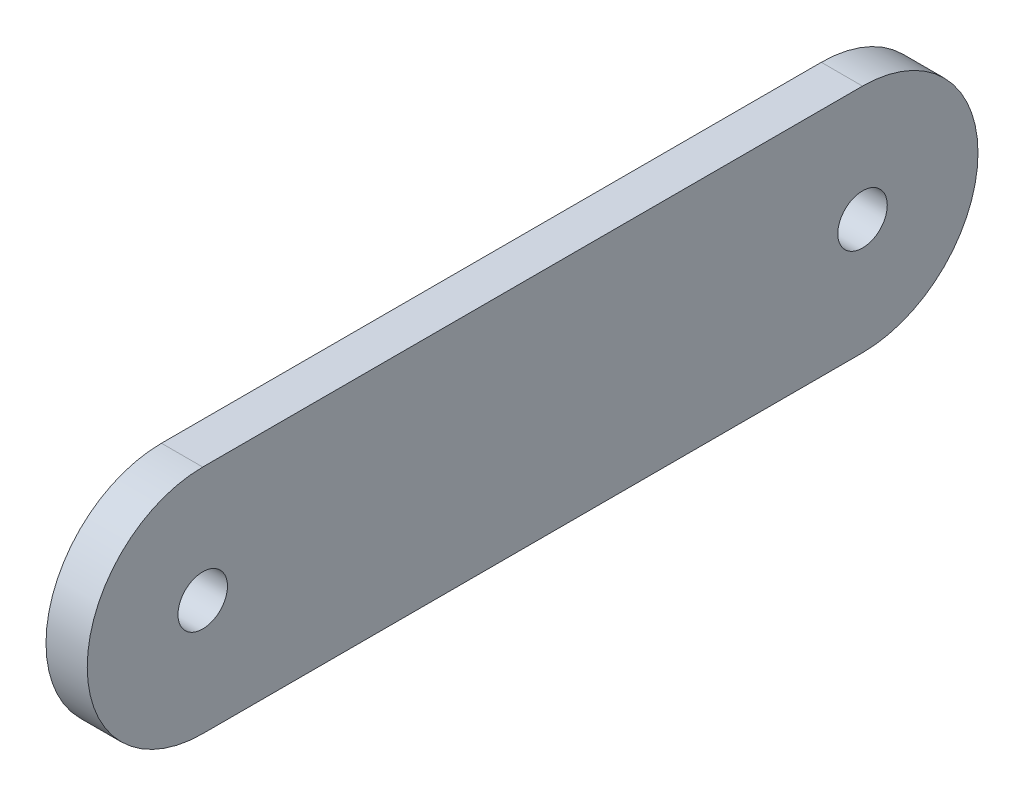
SolidWorks part; units mm, degrees
ref_plane "Ground" through (0, 0, 0) normal (0, 0, 1) x (1, 0, 0)
ref_plane "Right" through (0, 0, 0) normal (0, 1, 0) x (1, 0, 0)
ref_plane "Front" through (0, 0, 0) normal (1, 0, 0) x (0, 0, -1)
sketch "Sketch1" plane through (0, 0, 0) normal (1, 0, 0) x (0, 0, -1)
  line L0 (0, 0) -> (-40, 0) construction
  line L1 (0, -7) -> (-40, -7)
  line L2 (0, 7) -> (-40, 7)
  arc A0 (0, -7) -> (0, 7) centre (0, 0) ccw
  arc A1 (-40, 7) -> (-40, -7) centre (-40, 0) ccw
  circle A2 centre (-40, 0) radius 1.5
  circle A3 centre (0, 0) radius 1.5
  point P3 (-20, 0)
  dimension "D2" = 3
  dimension "D3" = 7
  dimension "D1" = 40
extrude "Boss-Extrude1" add sketch "Sketch1" along normal blind 2.5
